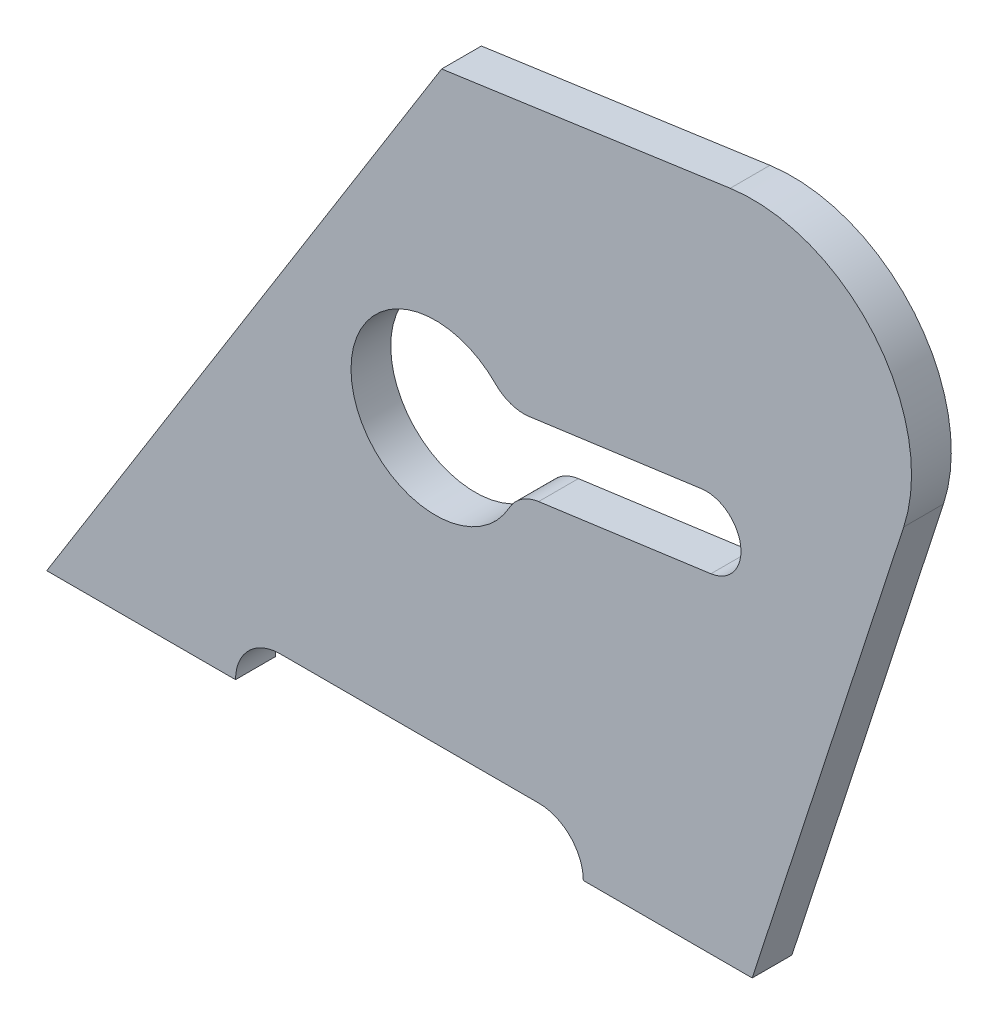
SolidWorks part; units mm, degrees
ref_plane "Płaszczyzna przednia" through (0, 0, 0) normal (0, 0, 1) x (1, 0, 0)
ref_plane "Płaszczyzna górna" through (0, 0, 0) normal (0, 1, 0) x (1, 0, 0)
ref_plane "Płaszczyzna prawa" through (0, 0, 0) normal (1, 0, 0) x (0, 0, -1)
sketch "Szkic1" plane through (0, 0, 0) normal (0, 0, 1) x (1, 0, 0)
  line L0 (0, 0) -> (38, 0)
  line L1 (47, 9) -> (99, 9)
  line L2 (108, 0) -> (142, 0)
  line L3 (142, 0) -> (172.5035, 93.8803)
  line L4 (137.573, 135.4513) -> (79.4879, 127.2072)
  line L5 (79.4879, 127.2072) -> (0, 0)
  line L6 (172.5035, 93.8803) -> (188.3525, 142.6585) construction
  line L7 (137.573, 135.4513) -> (188.3525, 142.6585) construction
  line L8 (142, 0) -> (167.3394, 77.9866) construction
  line L9 (0, 0) -> (37.6243, 60.2114) construction
  line L10 (37.6243, 60.2114) -> (167.3394, 77.9866) construction
  line L11 (131.7851, 80.1799) -> (97.1091, 75.4282)
  line L12 (133.6858, 66.3096) -> (99.0098, 61.5578)
  arc A0 (38, 0) -> (47, 9) centre (47, 0) cw
  arc A1 (99, 9) -> (108, 0) centre (99, 0) cw
  arc A2 (172.5035, 93.8803) -> (137.573, 135.4513) centre (142.0697, 103.7688) ccw
  circle A3 centre (78.2447, 65.7777) radius 17
  circle A4 centre (132.7354, 73.2448) radius 7
  arc A5 (93.1035, 57.5186) -> (99.0098, 61.5578) centre (100.0959, 53.6319) cw
  arc A6 (97.1091, 75.4282) -> (90.3339, 77.7297) centre (96.023, 83.3541) cw
  point P12 (-43.7194, 154.2103)
  dimension "D9" = 32
  dimension "D14" = 34
  dimension "D15" = 14
  dimension "D16" = 8
  dimension "D1" = 58
  dimension "D2" = 108
  dimension "D3" = 142
  dimension "D4" = 52
  dimension "D5" = 47
  dimension "D6" = 9
  dimension "D7" = 150
  dimension "D8" = 150
  dimension "D10" = 71
  dimension "D11" = 82
  dimension "D12" = 55
  dimension "D13" = 41
extrude "Dodanie-wyciągnięcie1" add sketch "Szkic1" along normal blind 8 contours L3 A2 L4 L5 L0 A0 L1 A1 L2 A6 L11 A4 L12 A5 A3
